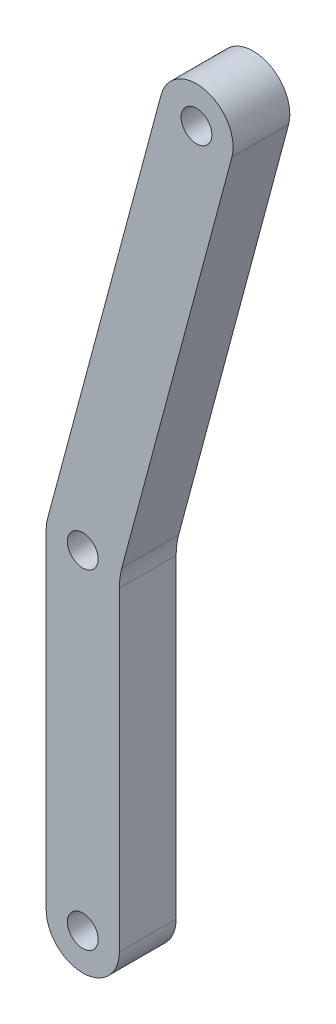
SolidWorks part; units mm, degrees
ref_plane "Plan de face" through (0, 0, 0) normal (0, 0, 1) x (1, 0, 0)
ref_plane "Plan de dessus" through (0, 0, 0) normal (0, 1, 0) x (1, 0, 0)
ref_plane "Plan de droite" through (0, 0, 0) normal (1, 0, 0) x (0, 0, -1)
sketch "Esquisse1" plane through (0, 0, 0) normal (0, 0, 1) x (1, 0, 0)
  line L0 (0, 0) -> (0, 45) construction
  line L1 (-5, 0) -> (-5, 45)
  line L2 (5, 0) -> (5, 45)
  line L3 (0, 45) -> (15.5291, 102.9555) construction
  line L4 (-4.8296, 46.2941) -> (10.6995, 104.2496)
  line L5 (4.8296, 43.7059) -> (20.3588, 101.6615)
  arc A0 (-5, 0) -> (5, 0) centre (0, 0) ccw
  arc A1 (5, 45) -> (-5, 45) centre (0, 45) ccw
  arc A2 (-4.8296, 46.2941) -> (4.8296, 43.7059) centre (0, 45) ccw
  arc A3 (20.3588, 101.6615) -> (10.6995, 104.2496) centre (15.5291, 102.9555) ccw
  circle A4 centre (0, 0) radius 2.1
  circle A5 centre (0, 45) radius 2.1
  circle A6 centre (15.5291, 102.9555) radius 2.1
  point P3 (0, 22.5)
  point P8 (7.7646, 73.9778)
  dimension "D5" = 4.2
  dimension "D6" = 4.2
  dimension "D7" = 4.2
  dimension "D1" = 60
  dimension "D2" = 45
  dimension "D3" = 165
  dimension "D4" = 10
extrude "Boss.-Extru.1" add sketch "Esquisse1" along normal blind 7.75 contours L5 A3 L4 A1 L2 A6 | A1 A2 L5 L2 A5 | A2 L1 A0 L2 L5 A4
fillet "Congé1" radius 10 1 edges at (5, 44.3417, 3.875)
